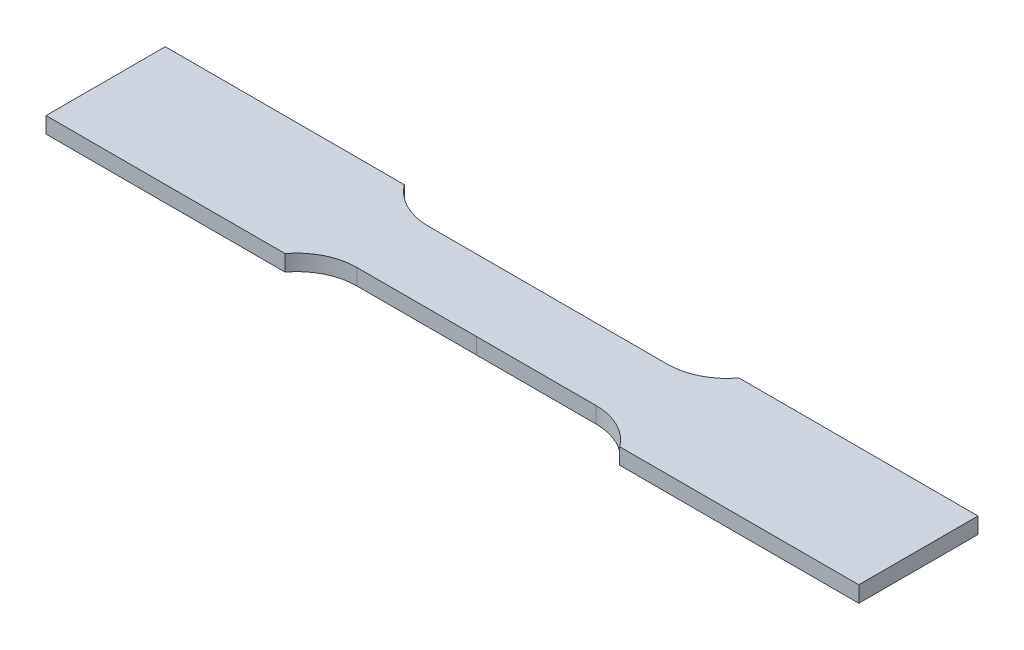
SolidWorks part; units mm, degrees
ref_plane "Front Plane" through (0, 0, 0) normal (0, 0, 1) x (1, 0, 0)
ref_plane "Top Plane" through (0, 0, 0) normal (0, 1, 0) x (1, 0, 0)
ref_plane "Right Plane" through (0, 0, 0) normal (1, 0, 0) x (0, 0, -1)
sketch "Sketch1" plane through (0, 0, 0) normal (0, 1, 0) x (1, 0, 0)
  line L3 (25, 7.47) -> (0, 7.475)
  line L4 (0, 7.475) -> (-25, 7.475)
  line L5 (-25, -7.475) -> (0, -7.475)
  line L6 (0, -7.475) -> (25, -7.47)
  line L7 (0, 7.475) -> (0, -7.475) construction
  line L8 (-25, 0) -> (25, 0) construction
  line L9 (25, 7.47) -> (25, 12.4667) construction
  line L10 (-35, 12.475) -> (-25, 12.475) construction
  line L11 (-25, 12.475) -> (-25, 7.475) construction
  line L12 (-25, -12.475) -> (-25, -7.475) construction
  line L13 (-35, 12.475) -> (-85, 12.475)
  line L15 (-35, -12.475) -> (-85, -12.475)
  line L16 (-85, 12.475) -> (-85, -12.475)
  line L17 (25, 12.4667) -> (35, 12.4667) construction
  line L18 (-35, -12.475) -> (-25, -12.475) construction
  line L19 (-25, 7.475) -> (-25, -7.475) construction
  line L20 (25, -7.47) -> (25, 7.47) construction
  line L22 (25, -7.47) -> (25, -12.4667) construction
  line L23 (25, -12.4667) -> (35, -12.4667) construction
  line L24 (35, 12.4667) -> (85, 12.4667)
  line L26 (35, -12.4667) -> (85, -12.4667)
  line L27 (85, 12.4667) -> (85, -12.4667)
  arc A0 (-35, 12.475) -> (-25, 7.475) centre (-25, 19.975) ccw
  arc A1 (-35, -12.475) -> (-25, -7.475) centre (-25, -19.975) cw
  arc A2 (35, -12.4667) -> (25, -7.47) centre (25.0025, -19.97) ccw
  arc A3 (35, 12.4667) -> (25, 7.47) centre (25.0025, 19.97) cw
  dimension "D5" = 25
  dimension "D9" = 25
  dimension "D4" = 14.95
  dimension "D6" = 10
  dimension "D8" = 50
  dimension "D1" = 14.95
  dimension "D2" = 14.94
  dimension "D3" = 50
  dimension "D10" = 10
  dimension "D11" = 50
extrude "Boss-Extrude2" add sketch "Sketch1" along normal blind 3.357 contours L24 A3 L3 L4 A0 L13 L16 L15 A1 L5 L6 A2 L26 L27
equation "\"D5@Sketch1\"=12.5*2"
equation "\"D9@Sketch1\"=12.5*2"
